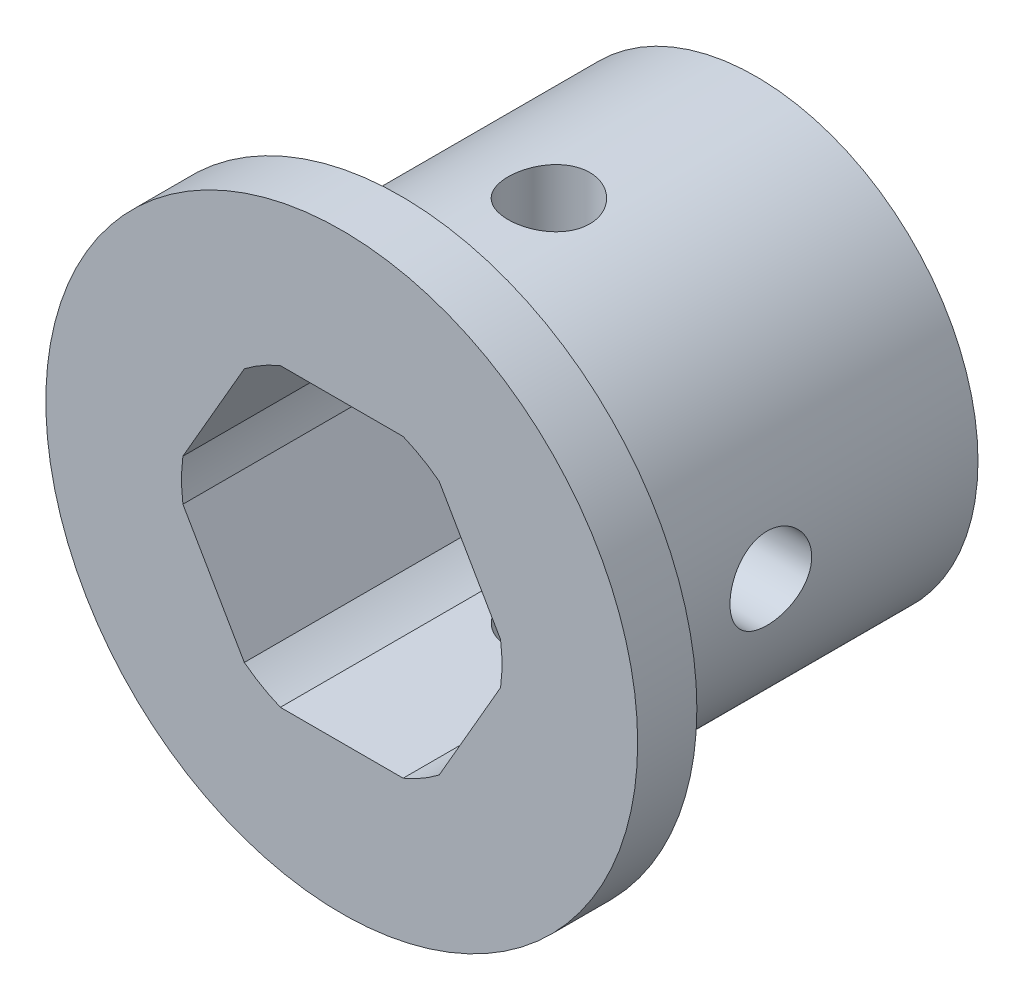
SolidWorks part; units mm, degrees
material "6061-T6 (SS)"
ref_plane "Front Plane" through (0, 0, 0) normal (0, 0, 1) x (1, 0, 0)
ref_plane "Top Plane" through (0, 0, 0) normal (0, 1, 0) x (1, 0, 0)
ref_plane "Right Plane" through (0, 0, 0) normal (1, 0, 0) x (0, 0, -1)
sketch "Sketch5" plane through (0, 0, 0) normal (0, 0, 1) x (1, 0, 0)
  circle A0 centre (0, 0) radius 9.525
  dimension "D1" = 19.05
extrude "Boss-Extrude1" add sketch "Sketch5" along normal blind 15.24
sketch "Sketch6" plane through (0, 0, 15.24) normal (0, 0, 1) x (1, 0, 0)
  circle A0 centre (0, 0) radius 12.7
  dimension "D1" = 25.4
extrude "Boss-Extrude2" add sketch "Sketch6" along normal blind 2.54
sketch "Sketch7" plane through (0, 0, 0) normal (0, 0, -1) x (-1, 0, 0)
  line L1 (3.6662, 6.35) -> (-3.6662, 6.35)
  line L2 (-3.6662, 6.35) -> (-7.3323, 0)
  line L3 (-7.3323, 0) -> (-3.6662, -6.35)
  line L4 (-3.6662, -6.35) -> (3.6662, -6.35)
  line L5 (3.6662, -6.35) -> (7.3323, 0)
  line L6 (7.3323, 0) -> (3.6662, 6.35)
  circle A0 centre (0, 0) radius 6.35 construction
  circle A1 centre (0, 0) radius 6.875
  point P10 (0, 0)
  dimension "D1" = 13.75
  dimension "D2" = 12.7
extrude "Cut-Extrude1" cut sketch "Sketch7" against normal through all contours L6 A1 L1 L2 L3 L4 L5
sketch "Sketch8" plane through (0, 0, 0) normal (1, 0, 0) x (0, 0, -1)
  line L0 (-15.24, -12.7) -> (-15.24, 12.7) construction
  line L2 (-8.89, 0) -> (-8.89, 9.525) construction
  line L5 (-8.89, 0) -> (-8.89, -9.525) construction
  line L6 (0, 9.525) -> (-15.24, 9.525) construction
  line L7 (-15.24, -9.525) -> (0, -9.525) construction
  circle A0 centre (-8.89, 0) radius 1.7526
  point P6 (-12.192, 0.2375)
  point P7 (0, 0)
  point P10 (0, 0)
  point P13 (0, 0)
  dimension "D1" = 3.5052
  dimension "D2" = 6.35
extrude "Cut-Extrude3" cut sketch "Sketch8" against normal through all both and the other way through all
sketch "Sketch9" plane through (0, 0, 0) normal (0, 1, 0) x (1, 0, 0)
  line L0 (-9.525, -8.89) -> (0, -8.89) construction
  line L1 (-9.525, 0) -> (-9.525, -7.1374) construction
  line L2 (0, -8.89) -> (9.525, -8.89) construction
  line L3 (9.525, -7.1374) -> (9.525, 0) construction
  line L4 (12.7, -15.24) -> (-12.7, -15.24) construction
  circle A0 centre (0, -8.89) radius 1.7526
  dimension "D1" = 3.5052
  dimension "D2" = 6.35
extrude "Cut-Extrude4" cut sketch "Sketch9" against normal through all both and the other way through all
equation "\"D1@Sketch7\"=13.75mm"
